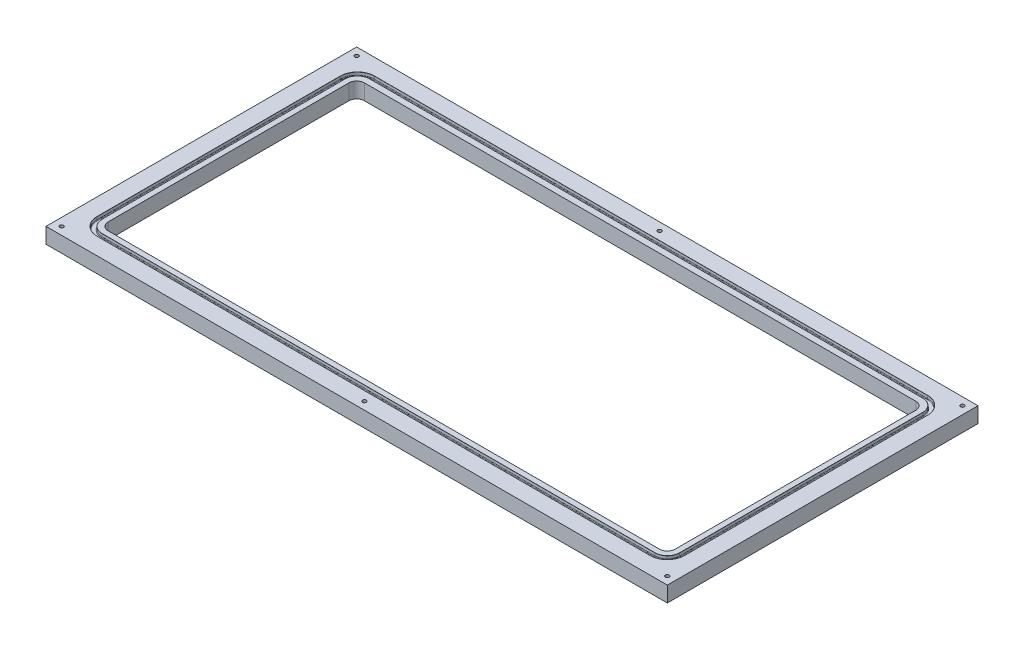
SolidWorks part; units mm, degrees
ref_plane "정면" through (0, 0, 0) normal (0, 0, 1) x (1, 0, 0)
ref_plane "윗면" through (0, 0, 0) normal (0, 1, 0) x (1, 0, 0)
ref_plane "우측면" through (0, 0, 0) normal (1, 0, 0) x (0, 0, -1)
sketch "스케치1" plane through (0, 0, 0) normal (0, 1, 0) x (1, 0, 0)
  line L1 (0, 0) -> (800, 0)
  line L2 (0, 0) -> (0, 400)
  line L3 (0, 400) -> (800, 400)
  line L4 (800, 0) -> (800, 400)
  dimension "D1" = 800
  dimension "D2" = 400
extrude "보스-돌출1" add sketch "스케치1" along normal blind 20
sketch "스케치2" plane through (0, 20, 0) normal (0, 1, 0) x (1, 0, 0)
  line L0 (0, 0) -> (800, 0) construction
  line L1 (43.997, 376) -> (756.003, 376) construction
  line L2 (25, 357.003) -> (25, 43.997) construction
  line L3 (43.997, 25) -> (756.003, 25) construction
  line L4 (775, 357.003) -> (775, 43.997) construction
  line L6 (0, 400) -> (0, 0) construction
  line L7 (800, 0) -> (800, 400) construction
  line L8 (43.997, 372.95) -> (756.003, 372.95)
  line L9 (771.95, 357.003) -> (771.95, 43.997)
  line L10 (43.997, 28.05) -> (756.003, 28.05)
  line L11 (28.05, 357.003) -> (28.05, 43.997)
  line L12 (43.997, 379.05) -> (756.003, 379.05)
  line L13 (778.05, 357.003) -> (778.05, 43.997)
  line L14 (43.997, 21.95) -> (756.003, 21.95)
  line L15 (21.95, 357.003) -> (21.95, 43.997)
  arc A0 (756.003, 376) -> (775, 357.003) centre (756.003, 357.003) cw construction
  arc A1 (756.003, 25) -> (775, 43.997) centre (756.003, 43.997) ccw construction
  arc A2 (25, 43.997) -> (43.997, 25) centre (43.997, 43.997) ccw construction
  arc A3 (43.997, 376) -> (25, 357.003) centre (43.997, 357.003) ccw construction
  arc A4 (756.003, 372.95) -> (771.95, 357.003) centre (756.003, 357.003) cw
  arc A5 (756.003, 28.05) -> (771.95, 43.997) centre (756.003, 43.997) ccw
  arc A6 (28.05, 43.997) -> (43.997, 28.05) centre (43.997, 43.997) ccw
  arc A7 (43.997, 372.95) -> (28.05, 357.003) centre (43.997, 357.003) ccw
  arc A8 (756.003, 379.05) -> (778.05, 357.003) centre (756.003, 357.003) cw
  arc A9 (756.003, 21.95) -> (778.05, 43.997) centre (756.003, 43.997) ccw
  arc A10 (21.95, 43.997) -> (43.997, 21.95) centre (43.997, 43.997) ccw
  arc A11 (43.997, 379.05) -> (21.95, 357.003) centre (43.997, 357.003) ccw
  dimension "D5" = 18.997
  dimension "D1" = 25
  dimension "D2" = 351
  dimension "D3" = 25
  dimension "D4" = 25
  dimension "D6" = 3.05
  dimension "D7" = 3.05
extrude "컷-돌출1" cut sketch "스케치2" against normal blind 4.2
fillet "필렛1" radius 0.13 16 edges at (32.7208, 20, -368.2792) (400, 20, -372.95) (767.2792, 20, -368.2792) (771.95, 20, -200.5) (767.2792, 20, -32.7208) (400, 20, -28.05) (32.7208, 20, -32.7208) (28.4074, 20, -372.5926) (400, 20, -379.05) (771.5926, 20, -372.5926) (778.05, 20, -200.5) (771.5926, 20, -28.4074) (400, 20, -21.95) (28.4074, 20, -28.4074) (28.05, 20, -200.5) (21.95, 20, -200.5)
fillet "필렛2" radius 0.7 16 edges at (28.05, 15.8, -200.5) (32.7208, 15.8, -368.2792) (400, 15.8, -372.95) (767.2792, 15.8, -368.2792) (771.95, 15.8, -200.5) (767.2792, 15.8, -32.7208) (400, 15.8, -28.05) (21.95, 15.8, -200.5) (28.4074, 15.8, -372.5926) (400, 15.8, -379.05) (771.5926, 15.8, -372.5926) (778.05, 15.8, -200.5) (771.5926, 15.8, -28.4074) (400, 15.8, -21.95) (32.7208, 15.8, -32.7208) (28.4074, 15.8, -28.4074)
sketch "스케치3" plane through (0, 20, 0) normal (0, 1, 0) x (1, 0, 0)
  line L0 (0, 0) -> (800, 0) construction
  line L1 (45, 365) -> (755, 365)
  line L2 (35, 355) -> (35, 45)
  line L3 (45, 35) -> (755, 35)
  line L4 (765, 355) -> (765, 45)
  line L5 (0, 400) -> (0, 0) construction
  line L6 (800, 0) -> (800, 400) construction
  arc A0 (35, 45) -> (45, 35) centre (45, 45) ccw
  arc A1 (45, 365) -> (35, 355) centre (45, 355) ccw
  arc A2 (755, 365) -> (765, 355) centre (755, 355) cw
  arc A3 (755, 35) -> (765, 45) centre (755, 45) ccw
  dimension "D5" = 10
  dimension "D1" = 35
  dimension "D2" = 330
  dimension "D3" = 35
  dimension "D4" = 35
extrude "컷-돌출2" cut sketch "스케치3" against normal through all
sketch "스케치4" plane through (0, 20, 0) normal (0, 1, 0) x (1, 0, 0)
  line L0 (0, 400) -> (0, 0) construction
  line L1 (0, 0) -> (800, 0) construction
  line L2 (800, 0) -> (800, 400) construction
  line L3 (400, 400) -> (400, 0) construction
  line L4 (800, 400) -> (0, 400) construction
  point P0 (10, 10)
  point P1 (10, 390)
  point P2 (790, 390)
  point P3 (790, 10)
  point P12 (400, 390)
  point P14 (400, 10)
  point P22 (400, 10)
  dimension "D1" = 10
  dimension "D2" = 10
  dimension "D3" = 380
  dimension "D4" = 10
hole_wizard "M6 나사 구멍1" positions "스케치4" profile "스케치5" tap size "M6" standard "ISO"
sketch "스케치5" plane through (10, 20, -10) normal (1, 0, 0) x (0, 0, 1)
  line L0 (0, 0) -> (0, 16.5022)
  line L1 (0, 16.5022) -> (2.5, 15)
  line L2 (2.5, 15) -> (2.5, 0)
  line L5 (2.5, 0) -> (0, 0)
  line L10 (0, 16.5022) -> (-2.5, 15) construction
  line L11 (0, -6.35) -> (0, 107.95) construction
  dimension "탭 드릴 지름" = 5
  dimension "탭 드릴 깊이" = 15
  dimension "드릴 각도" = 118
cosmetic thread "구멍 나사산1" parameters "D1"=10, "D2"=6
cosmetic thread "구멍 나사산2" parameters "D1"=10, "D2"=6
cosmetic thread "구멍 나사산3" parameters "D1"=10, "D2"=6
cosmetic thread "구멍 나사산4" parameters "D1"=10, "D2"=6
cosmetic thread "구멍 나사산5" parameters "D1"=10, "D2"=6
cosmetic thread "구멍 나사산6" parameters "D1"=10, "D2"=6
